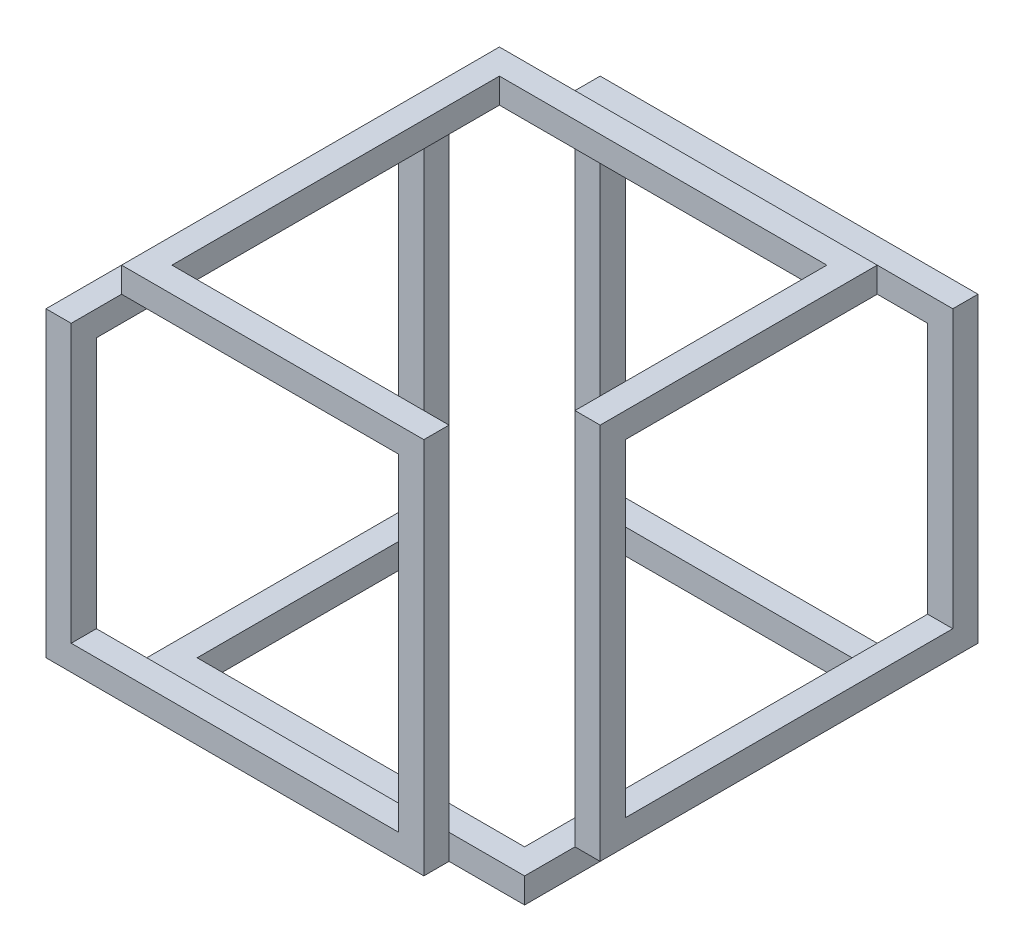
SolidWorks part; units mm, degrees
other "Annotazione1"
sketch "Schizzo15" plane through (75, -75, 0) normal (0.0224, -0.9996, -0.0152) x (0.9957, 0.021, 0.0908)
ref_plane "Piano frontale" through (0, 0, 0) normal (0, 0, 1) x (1, 0, 0)
ref_plane "Piano superiore" through (0, 0, 0) normal (0, 1, 0) x (1, 0, 0)
ref_plane "Piano destro" through (0, 0, 0) normal (1, 0, 0) x (0, 0, -1)
sketch "Schizzo1" plane through (0, 0, 0) normal (0, 0, 1) x (1, 0, 0)
  line L1 (45, -75) -> (-75, -75)
  line L2 (75, -45) -> (75, 75)
  line L3 (75, 75) -> (-75, 75)
  line L4 (-75, -75) -> (-75, 75)
  line L5 (75, -75) -> (-75, 75) construction
  line L6 (75, 75) -> (-75, -75) construction
  line L8 (45, -65) -> (-65, -65)
  line L9 (65, -45) -> (65, 65)
  line L10 (65, 65) -> (-65, 65)
  line L11 (-65, -65) -> (-65, 65)
  line L12 (65, -65) -> (-65, 65) construction
  line L13 (65, 65) -> (-65, -65) construction
  line L14 (45, -75) -> (45, -65)
  line L15 (75, -45) -> (65, -45)
  line L16 (75, -75) -> (-75, -75) construction
  line L17 (75, -75) -> (75, 75) construction
  line L19 (75, -45) -> (-75, -45) construction
  line L20 (45, -75) -> (45, 75) construction
  point P0 (0, 0)
  point P6 (0, 0)
  dimension "D1" = 150
  dimension "D2" = 150
  dimension "D3" = 130
  dimension "D4" = 130
  dimension "D5" = 30
  dimension "D6" = 30
extrude "Estrusione-Estrusione1" add sketch "Schizzo1" along normal blind 10
sketch "Schizzo10" plane through (0, 0, 10) normal (0, 0, 1) x (1, 0, 0)
  line L1 (45, -65) -> (-65, -65) construction
  line L2 (45, -75) -> (35, -75)
  line L3 (45, -75) -> (45, -65)
  line L4 (45, -65) -> (35, -65)
  line L5 (35, -75) -> (35, -65)
  dimension "D1" = 10
extrude "Estrusione-Estrusione4" add sketch "Schizzo10" along normal blind 140
sketch "Schizzo11" plane through (35, 0, 0) normal (-1, 0, 0) x (0, 0, 1)
  line L0 (150, -65) -> (10, -65) construction
  line L1 (150, -75) -> (140, -75)
  line L2 (150, -75) -> (150, -65)
  line L3 (150, -65) -> (140, -65)
  line L4 (140, -75) -> (140, -65)
  dimension "D1" = 10
extrude "Estrusione-Estrusione5" add sketch "Schizzo11" along normal blind 140
sketch "Schizzo12" plane through (0, 0, 140) normal (0, 0, -1) x (-1, 0, 0)
  line L0 (105, -75) -> (-35, -75) construction
  line L1 (105, -65) -> (95, -65)
  line L2 (105, -65) -> (105, -75)
  line L3 (105, -75) -> (95, -75)
  line L4 (95, -65) -> (95, -75)
  dimension "D1" = 10
extrude "Estrusione-Estrusione6" add sketch "Schizzo12" along normal blind 100
sketch "Schizzo13" plane through (0, -65, 0) normal (0, 1, 0) x (1, 0, 0)
  line L0 (-95, -40) -> (-95, -140) construction
  line L1 (-105, -40) -> (-95, -40)
  line L2 (-105, -40) -> (-105, -50)
  line L3 (-105, -50) -> (-95, -50)
  line L4 (-95, -40) -> (-95, -50)
  dimension "D1" = 10
extrude "Estrusione-Estrusione7" add sketch "Schizzo13" along normal blind 140
sketch "Schizzo16" plane through (0, 0, 10) normal (0, 0, 1) x (1, 0, 0)
  line L0 (65, 65) -> (65, -45) construction
  line L1 (75, -45) -> (65, -45)
  line L2 (75, -45) -> (75, -35)
  line L3 (75, -35) -> (65, -35)
  line L4 (65, -45) -> (65, -35)
  dimension "D1" = 10
extrude "Estrusione-Estrusione8" add sketch "Schizzo16" along normal blind 140
sketch "Schizzo17" plane through (0, -35, 0) normal (0, 1, 0) x (1, 0, 0)
  line L0 (65, -150) -> (65, -10) construction
  line L1 (75, -150) -> (65, -150)
  line L2 (75, -150) -> (75, -140)
  line L3 (75, -140) -> (65, -140)
  line L4 (65, -150) -> (65, -140)
  dimension "D1" = 10
extrude "Estrusione-Estrusione9" add sketch "Schizzo17" along normal blind 140
sketch "Schizzo19" plane through (0, 0, 140) normal (0, 0, -1) x (-1, 0, 0)
  line L0 (-65, 105) -> (-65, -35) construction
  line L1 (-75, 105) -> (-65, 105)
  line L2 (-75, 105) -> (-75, 95)
  line L3 (-75, 95) -> (-65, 95)
  line L4 (-65, 105) -> (-65, 95)
  dimension "D1" = 10
extrude "Estrusione-Estrusione10" add sketch "Schizzo19" along normal blind 100
sketch "Schizzo20" plane through (65, 0, 0) normal (-1, 0, 0) x (0, 0, 1)
  line L0 (40, 95) -> (140, 95) construction
  line L1 (40, 105) -> (50, 105)
  line L2 (40, 105) -> (40, 95)
  line L3 (40, 95) -> (50, 95)
  line L4 (50, 105) -> (50, 95)
  dimension "D1" = 10
extrude "Estrusione-Estrusione11" add sketch "Schizzo20" along normal blind 140
sketch "Schizzo21" plane through (0, 0, 50) normal (0, 0, 1) x (1, 0, 0)
  line L0 (-75, 95) -> (65, 95) construction
  line L1 (-75, 105) -> (-65, 105)
  line L2 (-75, 105) -> (-75, 95)
  line L3 (-75, 95) -> (-65, 95)
  line L4 (-65, 105) -> (-65, 95)
  dimension "D1" = 10
extrude "Estrusione-Estrusione12" add sketch "Schizzo21" along normal blind 140
sketch "Schizzo22" plane through (-65, 0, 0) normal (1, 0, 0) x (0, 0, -1)
  line L0 (-190, 95) -> (-50, 95) construction
  line L1 (-190, 105) -> (-180, 105)
  line L2 (-190, 105) -> (-190, 95)
  line L3 (-190, 95) -> (-180, 95)
  line L4 (-180, 105) -> (-180, 95)
  dimension "D1" = 10
extrude "Estrusione-Estrusione13" add sketch "Schizzo22" along normal blind 110
sketch "Schizzo23" plane through (0, 0, 50) normal (0, 0, 1) x (1, 0, 0)
  line L0 (-95, 75) -> (-95, -65) construction
  line L1 (-105, 75) -> (-95, 75)
  line L2 (-105, 75) -> (-105, 65)
  line L3 (-105, 65) -> (-95, 65)
  line L4 (-95, 75) -> (-95, 65)
  dimension "D1" = 10
extrude "Estrusione-Estrusione14" add sketch "Schizzo23" along normal blind 140
sketch "Schizzo24" plane through (0, 65, 0) normal (0, -1, 0) x (1, 0, 0)
  line L0 (-95, 190) -> (-95, 50) construction
  line L1 (-105, 190) -> (-95, 190)
  line L2 (-105, 190) -> (-105, 180)
  line L3 (-105, 180) -> (-95, 180)
  line L4 (-95, 190) -> (-95, 180)
  dimension "D1" = 10
extrude "Estrusione-Estrusione15" add sketch "Schizzo24" along normal blind 110
sketch "Schizzo25" plane through (-95, 0, 0) normal (1, 0, 0) x (0, 0, -1)
  line L0 (-180, -45) -> (-180, 65) construction
  line L1 (-190, -45) -> (-180, -45)
  line L2 (-190, -45) -> (-190, -35)
  line L3 (-190, -35) -> (-180, -35)
  line L4 (-180, -45) -> (-180, -35)
  dimension "D1" = 10
extrude "Estrusione-Estrusione16" add sketch "Schizzo25" along normal blind 140
sketch "Schizzo26" plane through (0, 95, 0) normal (0, -1, 0) x (1, 0, 0)
  line L0 (-75, 190) -> (45, 190) construction
  line L1 (45, 180) -> (35, 180)
  line L2 (45, 180) -> (45, 190)
  line L3 (45, 190) -> (35, 190)
  line L4 (35, 180) -> (35, 190)
  dimension "D1" = 10
extrude "Estrusione-Estrusione17" add sketch "Schizzo26" along normal blind 140
